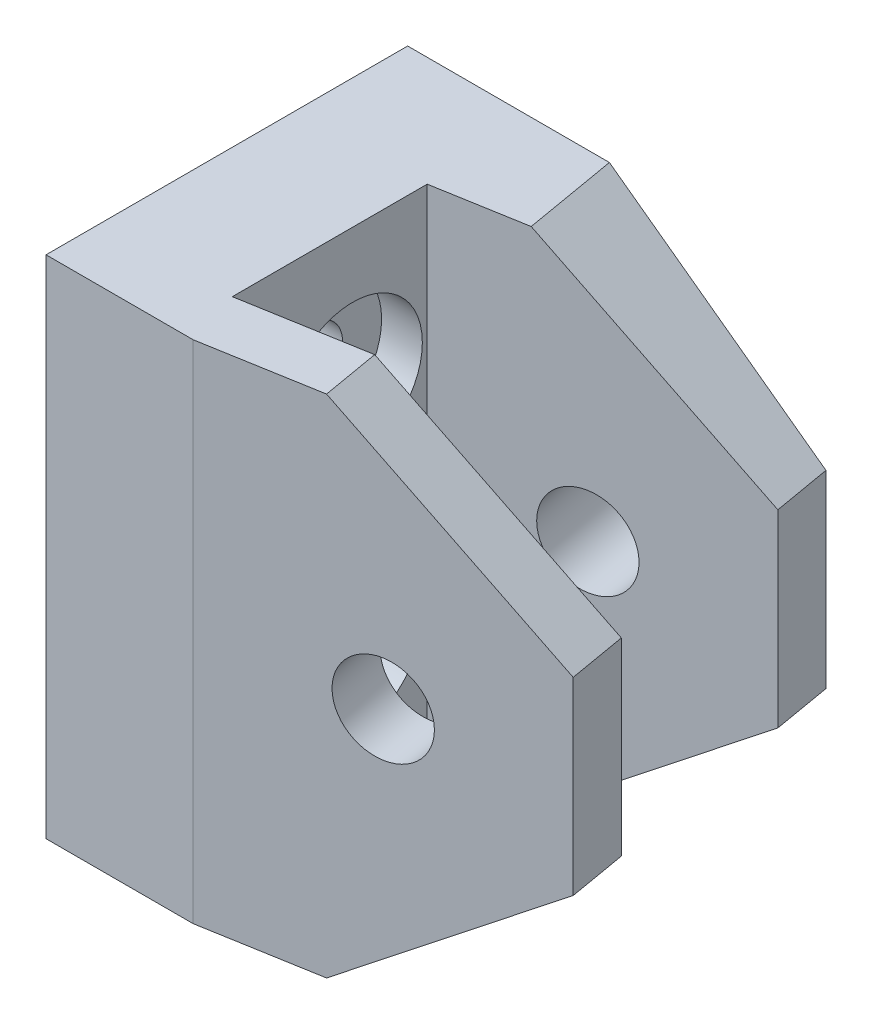
SolidWorks part; units mm, degrees
material "Custom Plastic"
ref_plane "X-Y Datum" through (0, 0, 0) normal (0, 0, 1) x (1, 0, 0)
ref_plane "X-Z Datum" through (0, 0, 0) normal (0, 1, 0) x (1, 0, 0)
ref_plane "Y-Z Datum" through (0, 0, 0) normal (1, 0, 0) x (0, 0, -1)
sketch "Sketch1" plane through (0, 0, 0) normal (0, 1, 0) x (1, 0, 0)
  line L0 (15.6309, -74.4973) -> (15.6309, -35.6112)
  line L1 (55.4851, -53.4201) -> (-12.3387, -65.1477) construction
  line L2 (66.2935, -68.4738) -> (31.4579, -74.4973)
  line L3 (65.2116, -62.2166) -> (29.5459, -68.3836)
  line L4 (29.5459, -68.3836) -> (29.5459, -47.427)
  line L5 (29.5459, -47.427) -> (61.6932, -41.8684)
  line L6 (61.6932, -41.8684) -> (60.6112, -35.6112)
  line L7 (60.6112, -35.6112) -> (15.6309, -35.6112)
  line L8 (31.4579, -74.4973) -> (15.6309, -74.4973)
  line L9 (65.2116, -62.2166) -> (66.2935, -68.4738)
  line L10 (47.3787, -54.8218) -> (44.9452, -40.7482) construction
  point P0 (47.3787, -54.8218)
  point P9 (29.5459, -57.9053)
  point P14 (0, 0)
  dimension "D1" = 20.6502
  dimension "D2" = 6.35
  dimension "D3" = 36.195
  dimension "D4" = 9.81
  dimension "D5" = 44.9804
  dimension "D6" = 6.35
extrude "Boss-Extrude1" add sketch "Sketch1" along normal blind 54.3789
sketch "Sketch2" plane through (13.4207, 0, 77.6161) normal (0.1704, 0, 0.9854) x (0.9854, 0, -0.1704)
  line L2 (18.3048, 0) -> (53.6574, 0) construction
  line L3 (30.7112, 0) -> (53.6574, 17.0294)
  line L4 (53.6574, 54.3789) -> (53.6574, 0) construction
  line L6 (53.6574, 37.3494) -> (30.7112, 54.3789)
  line L7 (18.3048, 54.3789) -> (53.6574, 54.3789) construction
  line L9 (30.7112, 0) -> (53.6574, 0)
  line L10 (53.6574, 0) -> (53.6574, 17.0294)
  line L11 (30.7112, 54.3789) -> (53.6574, 54.3789)
  line L12 (53.6574, 54.3789) -> (53.6574, 37.3494)
  circle A0 centre (35.9811, 27.1894) radius 4.7625
  point P0 (35.9811, 27.1894)
  dimension "D1" = 9.525
  dimension "D5" = 17.6763
  dimension "D2" = 28.575
  dimension "D3" = 27.1894
  dimension "D4" = 20.32
extrude "Cut-Extrude1" cut sketch "Sketch2" against normal through all both and the other way through all
sketch "Sketch3" plane through (15.6309, 0, 0) normal (-1, 0, 0) x (0, 0, 1)
  line L0 (35.6112, 0) -> (74.4973, 0) construction
  line L1 (74.4973, 54.3789) -> (74.4973, 0) construction
  point P0 (55.4473, 39.8894)
  point P1 (55.4473, 14.4894)
  dimension "D1" = 25.4
  dimension "D2" = 14.4894
  dimension "D3" = 19.05
hole_wizard "CBORE for M6 Hex Head Bolt1" positions "Sketch4" profile "Sketch5" counterbore size "M6" standard "ANSI Metric"
sketch "Sketch4" plane through (29.5459, 0, 0) normal (1, 0, 0) x (0, 0, -1)
  point P0 (-55.4473, 14.4894)
  point P3 (-55.4473, 39.8894)
sketch "Sketch5" plane through (29.5459, 14.4894, 55.4473) normal (0, 1, 0) x (0, 0, -1)
  line L0 (0, 0) -> (0, 16.002)
  line L1 (0, 16.002) -> (3.3, 14.0192)
  line L2 (3.3, 14.0192) -> (3.3, 4.38)
  line L3 (3.3, 4.38) -> (7.5, 4.38)
  line L4 (7.5, 4.38) -> (7.5, 0)
  line L5 (7.5, 0) -> (0, 0)
  line L10 (0, 16.002) -> (-3.3, 14.0192) construction
  line L11 (0, -6.35) -> (0, 107.95) construction
  dimension "Hole Dia." = 6.6
  dimension "Hole Depth" = 16.002
  dimension "C'Bore Dia." = 15
  dimension "C'Bore Depth" = 4.38
  dimension "Drill Angle" = 118
